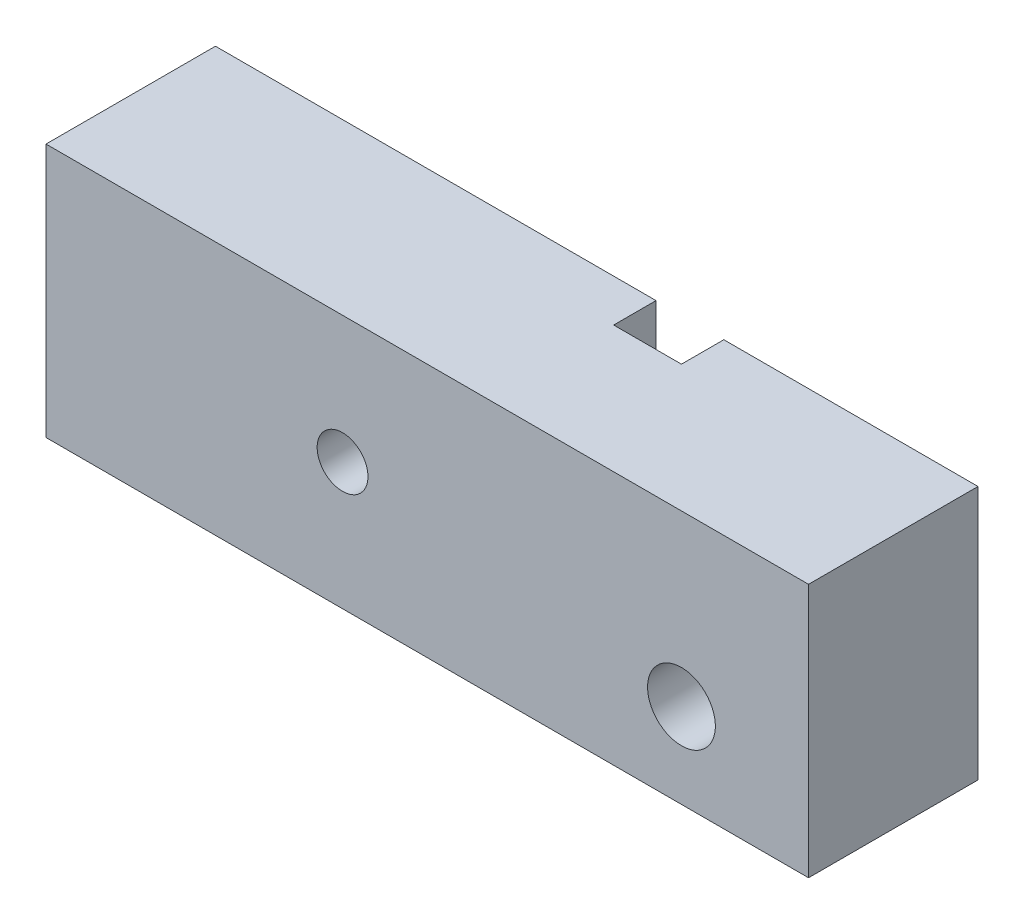
SolidWorks part; units mm, degrees
material "Сталь"
ref_plane "Спереди" through (0, 0, 0) normal (0, 0, 1) x (1, 0, 0)
ref_plane "Сверху" through (0, 0, 0) normal (0, 1, 0) x (1, 0, 0)
ref_plane "Справа" through (0, 0, 0) normal (1, 0, 0) x (0, 0, -1)
sketch "Эскиз1" plane through (0, 0, 0) normal (0, 0, 1) x (1, 0, 0)
  line L1 (-45, -15) -> (45, -15)
  line L2 (-45, -15) -> (-45, 15)
  line L3 (-45, 15) -> (45, 15)
  line L4 (45, -15) -> (45, 15)
  line L5 (-45, -15) -> (45, 15) construction
  line L6 (-45, 15) -> (45, -15) construction
  point P0 (0, 0)
  dimension "D1" = 30
  dimension "D2" = 90
extrude "Бобышка-Вытянуть1" add sketch "Эскиз1" along normal blind 20
sketch "Эскиз2" plane through (0, 0, 0) normal (0, 1, 0) x (1, 0, 0)
  line L0 (-30, 0) -> (-30, -20) construction
  line L1 (45, 0) -> (-45, 0) construction
  line L2 (45, -20) -> (-45, -20) construction
  line L3 (-45, -20) -> (-45, 0) construction
  line L4 (-30, 0) -> (-26, 0)
  line L5 (-26, 0) -> (-26, -10)
  line L6 (-26, -10) -> (-30, -14)
  line L7 (-30, 0) -> (-30, -14)
  dimension "D1" = 15
  dimension "D2" = 8
  dimension "D3" = 45
  dimension "D4" = 10
revolve "Вырез-Повернуть1" cut sketch "Эскиз2" angle 360 about L0
sketch "Эскиз3" plane through (0, 0, 0) normal (0, 0, -1) x (-1, 0, 0)
  line L0 (45, 15) -> (45, -15) construction
  circle A0 centre (10, 0) radius 6
  point P2 (45, 0)
  dimension "D2" = 12
  dimension "D1" = 35
extrude "Вырез-Вытянуть1" cut sketch "Эскиз3" against normal blind 12
sketch "Эскиз4" plane through (0, 0, 12) normal (0, 0, -1) x (-1, 0, 0)
  circle A0 centre (10, 0) radius 3
  dimension "D1" = 6
extrude "Вырез-Вытянуть2" cut sketch "Эскиз4" against normal through all
sketch "Эскиз5" plane through (0, 15, 0) normal (0, 1, 0) x (1, 0, 0)
  line L0 (45, 0) -> (-45, 0) construction
  line L1 (7, 0) -> (15, 0)
  line L2 (7, 0) -> (7, -5)
  line L3 (7, -5) -> (15, -5)
  line L4 (15, 0) -> (15, -5)
  line L5 (45, -20) -> (45, 0) construction
  dimension "D1" = 5
  dimension "D2" = 8
  dimension "D3" = 30
extrude "Вырез-Вытянуть3" cut sketch "Эскиз5" against normal through all
sketch "Эскиз6" plane through (0, 0, 0) normal (0, 0, -1) x (-1, 0, 0)
  line L0 (-15, -15) -> (-45, -15) construction
  line L1 (-45, -15) -> (-45, 15) construction
  circle A0 centre (-30, -5) radius 4
  dimension "D2" = 15
  dimension "D3" = 8
  dimension "D1" = 10
extrude "Вырез-Вытянуть4" cut sketch "Эскиз6" against normal through all
